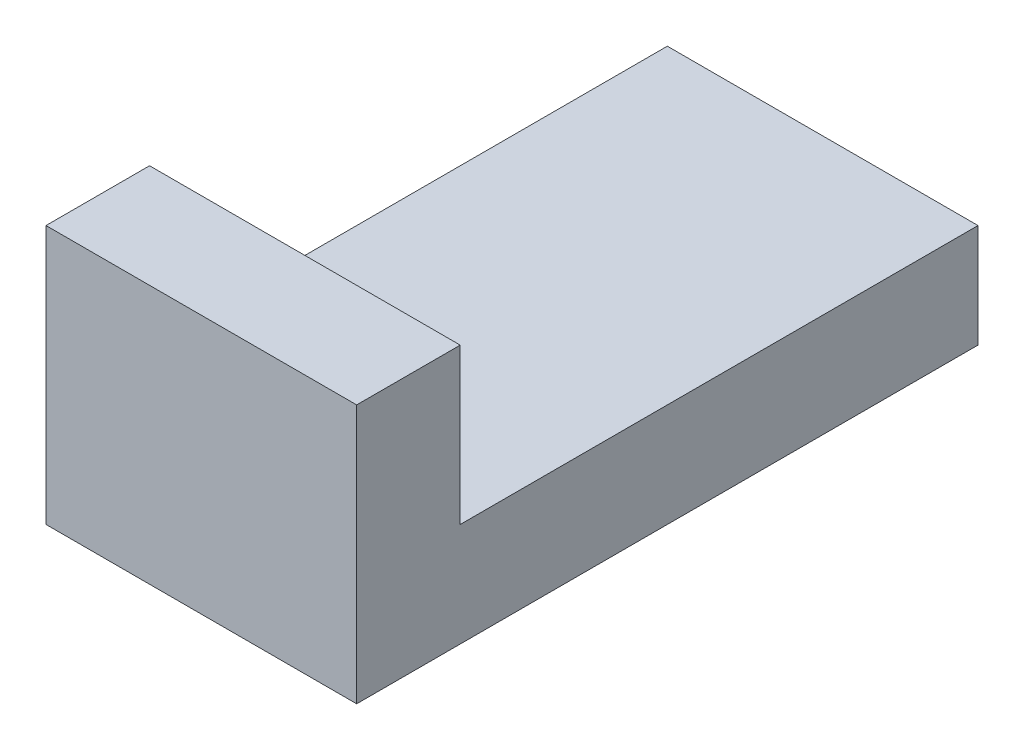
SolidWorks part; units mm, degrees
ref_plane "Front Plane" through (0, 0, 0) normal (0, 0, 1) x (1, 0, 0)
ref_plane "Top Plane" through (0, 0, 0) normal (0, 1, 0) x (1, 0, 0)
ref_plane "Right Plane" through (0, 0, 0) normal (1, 0, 0) x (0, 0, -1)
sketch "Sketch1" plane through (0, 0, 0) normal (1, 0, 0) x (0, 0, -1)
  line L0 (0, 25) -> (0, 0)
  line L1 (0, 0) -> (60, 0)
  dimension "D1" = 60
  dimension "D2" = 25
extrude "Extrude-Thin1" add sketch "Sketch1" along normal mid plane 30 thin thin type one direction reverse wall 10
